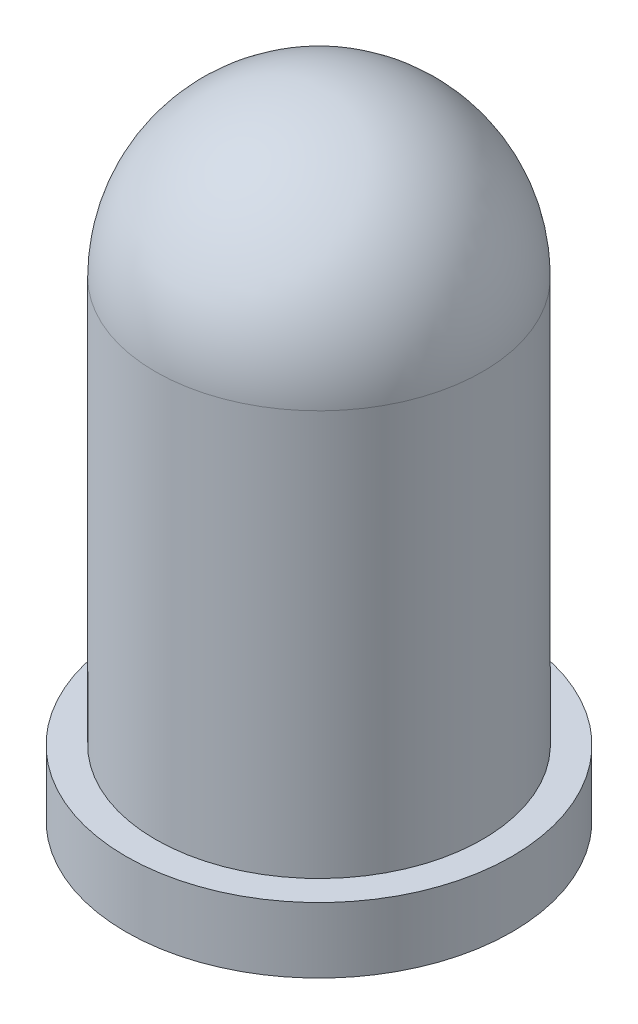
SolidWorks part; units mm, degrees
ref_plane "Front Plane" through (0, 0, 0) normal (0, 0, 1) x (1, 0, 0)
ref_plane "Top Plane" through (0, 0, 0) normal (0, 1, 0) x (1, 0, 0)
ref_plane "Right Plane" through (0, 0, 0) normal (1, 0, 0) x (0, 0, -1)
sketch "Sketch1" plane through (0, 0, 0) normal (0, 0, 1) x (1, 0, 0)
  line L0 (-2.5, 0) -> (-2.5, 6.19)
  line L1 (-2.246, 0) -> (-2.246, 6.19)
  line L2 (0, 8.69) -> (0, 8.436)
  line L3 (0, 0) -> (0, 8.69) construction
  line L4 (-2.246, 0) -> (-2.5, 0)
  arc A0 (-2.5, 6.19) -> (0, 8.69) centre (0, 6.19) cw
  arc A1 (-2.246, 6.19) -> (0, 8.436) centre (0, 6.19) cw
  dimension "D1" = 2.5
  dimension "D3" = 0.254
  dimension "D4" = 8.69
ref_axis "Axis1" through (0, 9.1245, 0) along (0, -1, 0)
revolve "Shell" add sketch "Sketch1" angle 360 about axis through (0, 9.1245, 0) along (0, -1, 0)
sketch "Sketch2" plane through (0, 0, 0) normal (0, 1, 0) x (1, 0, 0)
  circle A0 centre (0, 0) radius 2.95
  dimension "D1" = 5.9
extrude "Base" add sketch "Sketch2" against normal blind 1
sketch "Sketch4" plane through (0, 0, 0) normal (0, 1, 0) x (1, 0, 0)
  circle A0 centre (0, 0) radius 1.27
  dimension "D1" = 2.54
extrude "Diode" add sketch "Sketch4" along normal blind 5.08
